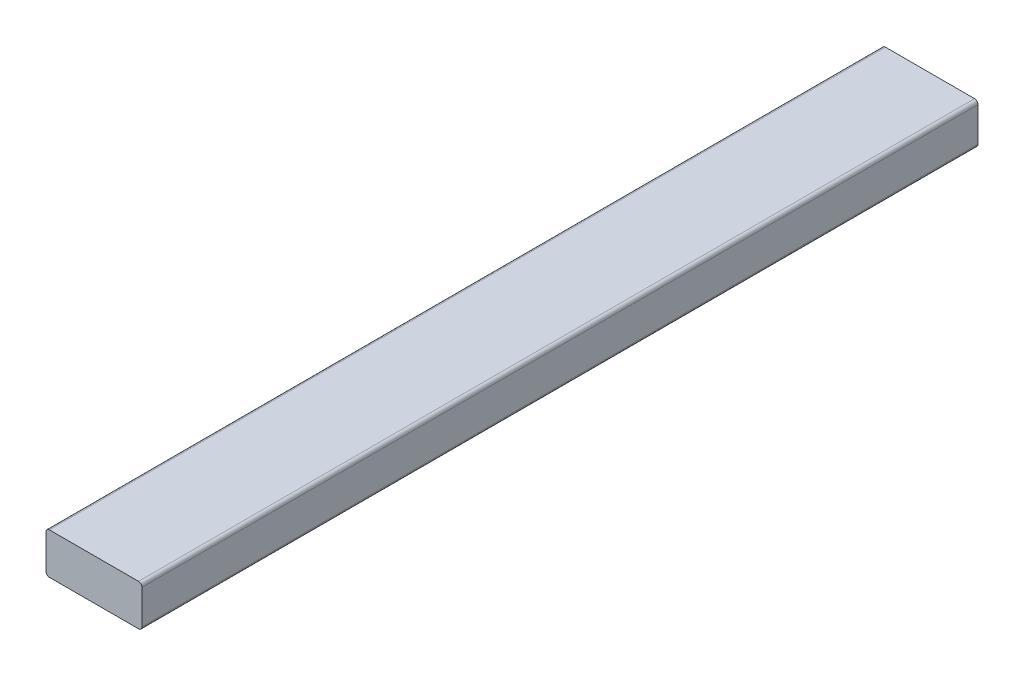
SolidWorks part; units mm, degrees
material "Pine"
ref_plane "Front Plane" through (0, 0, 0) normal (0, 0, 1) x (1, 0, 0)
ref_plane "Top Plane" through (0, 0, 0) normal (0, 1, 0) x (1, 0, 0)
ref_plane "Right Plane" through (0, 0, 0) normal (1, 0, 0) x (0, 0, -1)
sketch "Sketch1" plane through (0, 0, 0) normal (0, 0, 1) x (1, 0, 0)
  line L1 (-44.45, 19.05) -> (44.45, 19.05)
  line L2 (-44.45, 19.05) -> (-44.45, -19.05)
  line L3 (-44.45, -19.05) -> (44.45, -19.05)
  line L4 (44.45, 19.05) -> (44.45, -19.05)
  line L5 (0, -19.05) -> (0, 19.05) construction
  line L6 (-44.45, 0) -> (44.45, 0) construction
  point P0 (0, 0)
  dimension "D1" = 88.9
  dimension "D2" = 38.1
extrude "Boss-Extrude1" add sketch "Sketch1" along normal mid plane 774.7
fillet "Fillet1" radius 3.175 4 edges at (44.45, -19.05, 0) (-44.45, -19.05, 0) (-44.45, 19.05, 0) (44.45, 19.05, 0)
